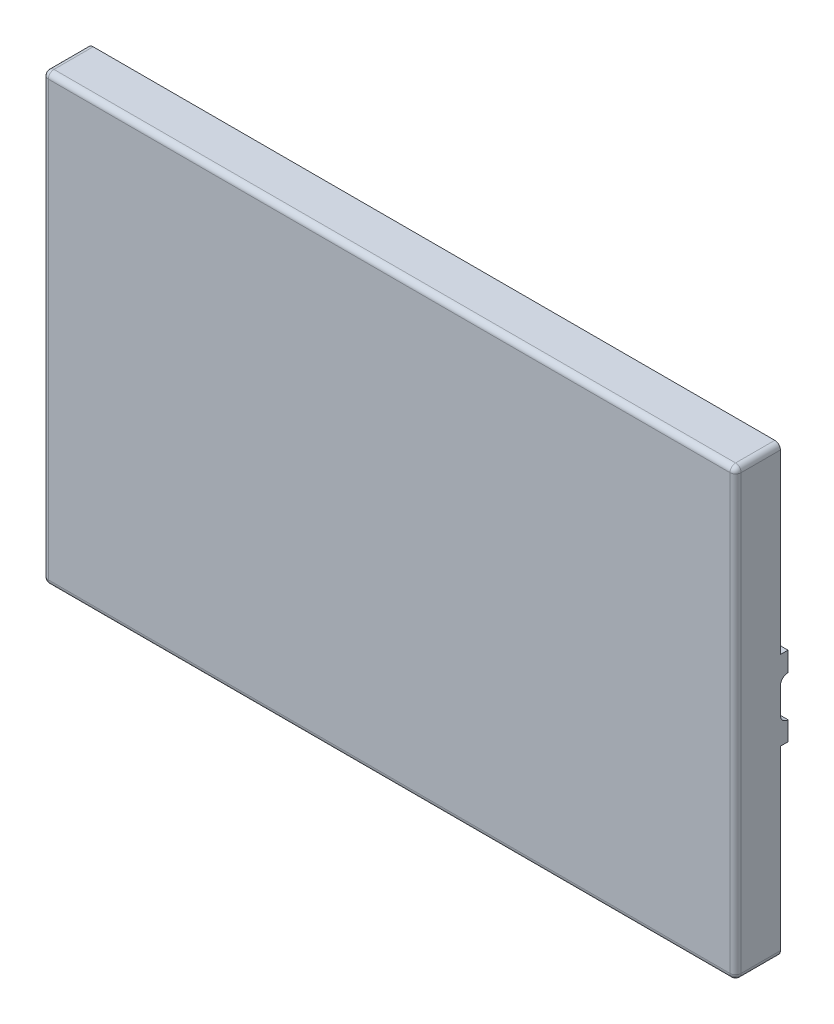
SolidWorks part; units mm, degrees
ref_plane "Front Plane" through (0, 0, 0) normal (0, 0, 1) x (1, 0, 0)
ref_plane "Top Plane" through (0, 0, 0) normal (0, 1, 0) x (1, 0, 0)
ref_plane "Right Plane" through (0, 0, 0) normal (1, 0, 0) x (0, 0, -1)
sketch "Sketch1" plane through (0, 0, 0) normal (0, 0, 1) x (1, 0, 0)
  line L1 (-63.6291, -87.8864) -> (-220.6429, -87.8864)
  line L2 (-63.6291, -87.8864) -> (-63.6291, -188.6926)
  line L3 (-63.6291, -188.6926) -> (-220.6429, -188.6926)
  line L4 (-220.6429, -87.8864) -> (-220.6429, -188.6926)
extrude "Boss-Extrude1" add sketch "Sketch1" along normal blind 10.16
sketch "Sketch2" plane through (0, 0, 0) normal (0, 0, -1) x (-1, 0, 0)
  line L8 (69.9791, -94.2364) -> (69.9791, -182.3426)
  line L9 (69.9791, -182.3426) -> (214.2929, -182.3426)
  line L10 (214.2929, -182.3426) -> (214.2929, -94.2364)
  line L11 (214.2929, -94.2364) -> (69.9791, -94.2364)
  line L12 (69.9791, -94.2364) -> (69.9791, -182.3426)
  line L13 (69.9791, -182.3426) -> (214.2929, -182.3426)
  line L14 (214.2929, -182.3426) -> (214.2929, -94.2364)
  line L15 (214.2929, -94.2364) -> (69.9791, -94.2364)
  dimension "D1" = 6.35
extrude "Cut-Extrude1" cut sketch "Sketch2" against normal blind 3.81
sketch "Sketch3" plane through (0, 0, 3.81) normal (0, 0, -1) x (-1, 0, 0)
  circle A6 centre (109.2991, -111.9901) radius 1.373
  circle A7 centre (156.2491, -111.9901) radius 1.373
  circle A8 centre (156.2491, -136.5001) radius 1.373
  circle A9 centre (109.2991, -136.5001) radius 1.373
  dimension "D1" = 2.746
  dimension "D2" = 2.746
  dimension "D3" = 2.746
  dimension "D4" = 2.746
extrude "Boss-Extrude2" add sketch "Sketch3" along normal blind 13.208
sketch "Sketch4" plane through (0, 0, 3.81) normal (0, 0, -1) x (-1, 0, 0)
  line L0 (106.1041, -98.8201) -> (207.7041, -98.8201) construction
  line L9 (112.4541, -105.1701) -> (191.2741, -105.1701)
  line L10 (112.4541, -105.1701) -> (112.4541, -143.2701)
  line L11 (112.4541, -143.2701) -> (201.3541, -143.2701)
  line L12 (201.3541, -110.2701) -> (201.3541, -143.2701)
  line L18 (106.1041, -149.6201) -> (106.1041, -98.8201) construction
  line L21 (207.7041, -98.8201) -> (207.7041, -149.6201) construction
  line L23 (152.8358, -98.8201) -> (152.8358, -105.1701) construction
  line L25 (207.7041, -122.8794) -> (201.3541, -122.8794) construction
  line L26 (112.4541, -122.0504) -> (106.1041, -122.0504) construction
  line L28 (154.4491, -108.8151) -> (115.6291, -108.8151)
  line L29 (154.4491, -108.8151) -> (154.4491, -139.6751)
  line L30 (154.4491, -139.6751) -> (115.6291, -139.6751)
  line L31 (115.6291, -108.8151) -> (115.6291, -139.6751)
  line L35 (191.2741, -105.1701) -> (191.2741, -110.2701)
  line L36 (191.2741, -110.2701) -> (201.3541, -110.2701)
  line L38 (201.1801, -107.7301) -> (199.1481, -107.7301) construction
  line L39 (193.8141, -107.4761) -> (193.8141, -105.4441) construction
  circle A6 centre (109.2991, -111.9901) radius 1.905
  circle A7 centre (109.2991, -136.5001) radius 1.905
  circle A11 centre (117.2591, -111.5201) radius 0.51 construction
  circle A12 centre (152.8191, -111.5201) radius 0.51 construction
  dimension "D2" = 6.35
  dimension "D3" = 6.35
  dimension "D4" = 6.35
  dimension "D14" = 2.54
  dimension "D6" = 3.81
  dimension "D7" = 3.81
  dimension "D8" = 1.63
  dimension "D9" = 1.63
  dimension "D10" = 3.645
  dimension "D11" = 3.175
  dimension "D12" = 2.54
  dimension "D15" = 3.595
extrude "Boss-Extrude3" add sketch "Sketch4" along normal blind 3.556
sketch "Sketch5" plane through (0, -87.8864, 0) normal (0, 1, 0) x (1, 0, 0)
  line L0 (-63.6291, 0) -> (-220.6429, 0) construction
  line L1 (-211.1977, 23.3785) -> (-70.747, 23.3785)
  line L2 (-211.1977, 23.3785) -> (-211.1977, 2.3813)
  line L3 (-211.1977, 2.3813) -> (-70.747, 2.3812)
  line L4 (-70.747, 23.3785) -> (-70.747, 2.3812)
  dimension "D1" = 2.3813
extrude "Cut-Extrude2" cut sketch "Sketch5" against normal blind 61.722
sketch "Sketch6" plane through (0, 0, 3.81) normal (0, 0, -1) x (-1, 0, 0)
  line L1 (69.9791, -182.3426) -> (73.1541, -182.3426)
  line L2 (69.9791, -182.3426) -> (69.9791, -179.1676)
  line L3 (69.9791, -179.1676) -> (73.1541, -179.1676)
  line L4 (73.1541, -182.3426) -> (73.1541, -179.1676)
  dimension "D1" = 3.175
  dimension "D2" = 3.175
extrude "Boss-Extrude4" add sketch "Sketch6" along normal blind 6.985
sketch "Sketch7" plane through (0, 0, -3.175) normal (0, 0, -1) x (-1, 0, 0)
  line L1 (73.1541, -179.1676) -> (71.5666, -179.1676)
  line L2 (73.1541, -179.1676) -> (73.1541, -180.7551)
  line L3 (73.1541, -180.7551) -> (71.5666, -180.7551)
  line L4 (71.5666, -179.1676) -> (71.5666, -180.7551)
  dimension "D1" = 1.5875
  dimension "D2" = 1.5875
extrude "Cut-Extrude3" cut sketch "Sketch7" against normal blind 6.985
ref_plane "Plane1" through (0, -138.2895, 0) normal (0, -1, 0) x (-1, 0, 0)
mirror "Mirror1" about plane through (0, -138.2895, 0) normal (0, -1, 0) of "Cut-Extrude3", "Boss-Extrude4"
ref_plane "Plane2" through (-142.136, 0, 0) normal (1, 0, 0) x (0, 0, -1)
mirror "Mirror2" about plane through (-142.136, 0, 0) normal (1, 0, 0) of "Mirror1", "Cut-Extrude3", "Boss-Extrude4"
sketch "Sketch8" plane through (0, 0, -3.175) normal (0, 0, -1) x (-1, 0, 0)
  line L0 (69.9791, -179.1676) -> (70.1775, -179.1676)
  line L1 (71.5666, -179.1676) -> (69.9791, -179.1676) construction
  line L2 (70.1775, -179.1676) -> (70.1775, -182.1442)
  line L3 (70.1775, -182.1442) -> (73.1541, -182.1442)
  line L4 (73.1541, -182.3426) -> (73.1541, -180.7551) construction
  line L5 (73.1541, -182.1442) -> (73.1541, -182.3426)
  line L6 (73.1541, -182.3426) -> (69.9791, -182.3426)
  line L7 (69.9791, -182.3426) -> (69.9791, -179.1676)
  dimension "D1" = 0.1984
  dimension "D2" = 0.1984
extrude "Cut-Extrude4" cut sketch "Sketch8" against normal up to surface (3.175 mm away) up to face at (-142.136, -138.2895, 0)
mirror "Mirror3" about plane through (-142.136, 0, 0) normal (1, 0, 0) of "Cut-Extrude4" second plane through (0, -138.2895, 0) second plane normal (0, -1, 0)
fillet "Fillet1" radius 1.27 8 edges at (-63.6291, -188.6926, 5.08) (-142.136, -188.6926, 10.16) (-220.6429, -188.6926, 5.08) (-220.6429, -138.2895, 10.16) (-220.6429, -87.8864, 5.08) (-142.136, -87.8864, 10.16) (-63.6291, -138.2895, 10.16) (-63.6291, -87.8864, 5.08)
sketch "Sketch9" plane through (0, 0, 3.81) normal (0, 0, -1) x (-1, 0, 0)
  line L0 (204.371, -174.0082) -> (180.5585, -174.0082)
  line L1 (204.371, -174.0082) -> (204.371, -158.1332)
  line L2 (204.371, -158.1332) -> (180.5585, -158.1332)
  line L3 (180.5585, -174.0082) -> (180.5585, -158.1332)
  line L4 (214.2929, -179.1676) -> (214.2929, -97.4114) construction
  line L5 (73.1541, -182.3426) -> (211.1179, -182.3426) construction
  dimension "D1" = 15.875
  dimension "D2" = 9.9219
  dimension "D3" = 8.3344
extrude "Boss-Extrude5" add sketch "Sketch9" along normal blind 11.4935
sketch "Sketch10" plane through (-63.6291, 0, 0) normal (1, 0, 0) x (0, 0, -1)
  line L0 (0, -187.4226) -> (0, -89.1564) construction
  line L1 (-0.7937, -129.1614) -> (8.4675, -129.1614)
  line L2 (-0.7937, -129.1614) -> (-0.7937, -147.4176)
  line L3 (-0.7937, -147.4176) -> (8.4675, -147.4176)
  line L4 (8.4675, -129.1614) -> (8.4675, -147.4176)
  line L5 (0, -89.1564) -> (-8.89, -89.1564) construction
  line L6 (-0.7937, -129.1614) -> (-0.7937, -89.1564) construction
  line L7 (-0.7937, -147.4176) -> (-0.7937, -187.4226) construction
  line L8 (-8.89, -187.4226) -> (0, -187.4226) construction
  dimension "D1" = 18.2562
  dimension "D2" = 0.7937
extrude "Cut-Extrude5" cut sketch "Sketch10" against normal blind 13.97 from offset 1.5875 offset against normal yes
sketch "Sketch12" plane through (0, 0, 3.81) normal (0, 0, -1) x (-1, 0, 0)
  line L1 (69.9791, -129.1614) -> (87.7591, -129.1614)
  line L2 (69.9791, -129.1614) -> (69.9791, -147.4176)
  line L3 (69.9791, -147.4176) -> (87.7591, -147.4176)
  line L4 (87.7591, -129.1614) -> (87.7591, -147.4176)
  dimension "D1" = 17.78
extrude "Boss-Extrude6" add sketch "Sketch12" along normal up to surface (3.0162 mm away) up to face at (-67.5979, -138.2895, 0.7937)
sketch "Sketch13" plane through (0, 0, 3.81) normal (0, 0, -1) x (-1, 0, 0)
  line L1 (91.6754, -134.2414) -> (94.8504, -134.2414)
  line L2 (91.6754, -134.2414) -> (91.6754, -142.3376)
  line L3 (91.6754, -142.3376) -> (94.8504, -142.3376)
  line L4 (94.8504, -134.2414) -> (94.8504, -142.3376)
  line L5 (87.7591, -129.1614) -> (101.5052, -129.1614) construction
  line L6 (87.7591, -147.4176) -> (99.914, -147.4176) construction
  line L7 (93.2629, -142.3376) -> (93.2629, -147.4176) construction
  line L8 (93.2629, -129.1614) -> (93.2629, -134.2414) construction
  line L9 (87.7591, -129.1614) -> (87.7591, -147.4176) construction
  dimension "D1" = 3.9162
  dimension "D2" = 3.175
  dimension "D3" = 5.08
extrude "Boss-Extrude7" add sketch "Sketch13" along normal blind 5.08
sketch "Sketch14" plane through (-63.6291, 0, 0) normal (1, 0, 0) x (0, 0, -1)
  line L6 (0, -129.2884) -> (0, -135.4466)
  line L7 (0, -187.4226) -> (0, -89.1564) construction
  line L10 (0, -147.2906) -> (1.7169, -147.2906)
  line L11 (1.7169, -147.2906) -> (1.7169, -142.9435)
  line L12 (0, -141.2266) -> (0, -147.2906)
  line L13 (1.7169, -133.7297) -> (1.7169, -129.2884)
  line L14 (1.7169, -129.2884) -> (0, -129.2884)
  line L15 (3.4337, -135.4466) -> (1.2516, -135.4466) construction
  line L17 (3.4337, -141.2266) -> (2.7224, -141.2266) construction
  arc A1 (1.7169, -142.9435) -> (0, -141.2266) centre (1.7169, -141.2266) cw
  arc A2 (1.7169, -133.7297) -> (0, -135.4466) centre (1.7169, -135.4466) ccw
  dimension "D1" = 6.1583
  dimension "D2" = 6.064
extrude "Boss-Extrude9" add sketch "Sketch14" against normal up to surface (1.5875 mm away) up to face at (-65.2166, -138.2895, 0.3969)
sketch "Sketch17" plane through (0, 0, 3.81) normal (0, 0, -1) x (-1, 0, 0)
  line L0 (155.5098, -182.3426) -> (155.5098, -174.0082) construction
  line L1 (155.1585, -170.1982) -> (155.1585, -152.7834) construction
  line L2 (180.5585, -158.1332) -> (180.5585, -174.0082) construction
  line L3 (142.4585, -174.0082) -> (167.8585, -174.0082)
  line L4 (142.4585, -174.0082) -> (142.4585, -170.1982)
  line L5 (142.4585, -170.1982) -> (167.8585, -170.1982)
  line L6 (167.8585, -174.0082) -> (167.8585, -170.1982)
  line L7 (142.4585, -152.7834) -> (167.8585, -152.7834)
  line L8 (142.4585, -152.7834) -> (142.4585, -148.9734)
  line L9 (142.4585, -148.9734) -> (167.8585, -148.9734)
  line L10 (167.8585, -152.7834) -> (167.8585, -148.9734)
  line L11 (73.1541, -182.3426) -> (211.1179, -182.3426) construction
  line L12 (73.1541, -182.3426) -> (211.1179, -182.3426) construction
  line L13 (136.545, -161.4908) -> (173.7719, -161.4908) construction
  line L14 (173.7719, -158.3158) -> (177.5819, -158.3158)
  line L15 (173.7719, -158.3158) -> (173.7719, -164.6658)
  line L16 (173.7719, -164.6658) -> (177.5819, -164.6658)
  line L17 (177.5819, -158.3158) -> (177.5819, -164.6658)
  line L18 (132.735, -158.3158) -> (136.545, -158.3158)
  line L19 (132.735, -158.3158) -> (132.735, -164.6658)
  line L20 (132.735, -164.6658) -> (136.545, -164.6658)
  line L21 (136.545, -158.3158) -> (136.545, -164.6658)
  line L23 (142.4585, -152.7834) -> (142.4585, -170.1982) construction
  line L24 (167.8585, -152.7834) -> (167.8585, -170.1982) construction
  line L25 (136.545, -159.4524) -> (142.4585, -159.4524) construction
  line L26 (167.8585, -160.6282) -> (173.7719, -160.6282) construction
  point P34 (136.545, -161.4908)
  point P35 (155.1585, -161.4908)
  point P36 (155.1585, -161.4908)
  dimension "D1" = 12.7
  dimension "D2" = 8.3344
  dimension "D3" = 3.81
  dimension "D4" = 3.81
  dimension "D5" = 17.4149
  dimension "D6" = 25.4
  dimension "D7" = 37.2269
  dimension "D8" = 3.81
  dimension "D9" = 6.35
extrude "Boss-Extrude10" add sketch "Sketch17" along normal blind 5.3658
sketch "Sketch18" plane through (0, 0, 3.81) normal (0, 0, -1) x (-1, 0, 0)
  line L0 (136.545, -152.7834) -> (155.595, -152.7834)
  line L1 (136.545, -152.7834) -> (136.545, -170.1982)
  line L2 (136.545, -170.1982) -> (155.595, -170.1982)
  line L3 (155.595, -152.7834) -> (155.595, -170.1982)
  line L4 (167.8585, -170.1982) -> (142.4585, -170.1982) construction
  line L6 (136.545, -164.6658) -> (136.545, -158.3158) construction
  line L7 (142.4585, -152.7834) -> (167.8585, -152.7834) construction
  line L8 (167.4219, -152.7834) -> (173.7719, -152.7834)
  line L9 (167.4219, -152.7834) -> (167.4219, -170.1982)
  line L10 (167.4219, -170.1982) -> (173.7719, -170.1982)
  line L11 (173.7719, -152.7834) -> (173.7719, -170.1982)
  line L12 (173.7719, -158.3158) -> (173.7719, -164.6658) construction
  dimension "D1" = 19.05
  dimension "D2" = 6.35
extrude "Boss-Extrude11" add sketch "Sketch18" along normal up to surface (3.556 mm away) up to face at (-157.6221, -111.9901, 0.254)
sketch "Sketch19" plane through (0, -188.6926, 0) normal (0, -1, 0) x (1, 0, 0)
  line L0 (-219.3729, 0) -> (-64.8991, 0) construction
  line L1 (-151.038, -4.3498) -> (-164.8493, -4.3498)
  line L2 (-151.038, -4.3498) -> (-151.038, 0)
  line L3 (-151.038, 0) -> (-164.8493, 0)
  line L4 (-164.8493, -4.3498) -> (-164.8493, 0)
  line L5 (-164.8493, -2.1749) -> (-170.7706, -2.1749) construction
  line L6 (-170.7706, 0) -> (-170.7706, -10.4775) construction
  line L7 (-151.038, -2.1749) -> (-145.1166, -2.1749) construction
  line L8 (-145.1166, -10.4775) -> (-145.1166, 0) construction
  dimension "D1" = 4.3498
  dimension "D2" = 13.8113
  dimension "D3" = 5.9214
extrude "Boss-Extrude12" add sketch "Sketch19" against normal up to surface (6.35 mm away) up to face at (-142.136, -182.3426, 1.905)
sketch "Sketch21" plane through (0, 0, 0) normal (0, 0, -1) x (-1, 0, 0)
  line L0 (73.1541, -182.3426) -> (151.038, -182.3426) construction
  line L1 (151.038, -188.6926) -> (145.2436, -188.6926)
  line L2 (151.038, -188.6926) -> (151.038, -182.3426)
  line L3 (151.038, -182.3426) -> (145.2436, -182.3426)
  line L4 (145.2436, -188.6926) -> (145.2436, -182.3426)
  line L5 (164.8493, -182.3426) -> (211.1179, -182.3426) construction
  line L6 (164.8493, -188.6926) -> (170.6436, -188.6926)
  line L7 (164.8493, -188.6926) -> (164.8493, -182.3426)
  line L8 (164.8493, -182.3426) -> (170.6436, -182.3426)
  line L9 (170.6436, -188.6926) -> (170.6436, -182.3426)
  dimension "D1" = 5.7944
  dimension "D2" = 5.7944
  dimension "D3" = 25.4
extrude "Boss-Extrude13" add sketch "Sketch21" along normal up to surface (10.4775 mm away)
sketch "Sketch22" plane through (0, 0, -10.4775) normal (0, 0, -1) x (-1, 0, 0)
  line L0 (157.9436, -185.1207) -> (157.9436, -182.3426) construction
  line L1 (148.0218, -185.1207) -> (167.8655, -185.1207)
  line L2 (148.0218, -185.1207) -> (148.0218, -185.9145)
  line L3 (148.0218, -185.9145) -> (167.8655, -185.9145)
  line L4 (167.8655, -185.1207) -> (167.8655, -185.9145)
  line L5 (151.038, -182.3426) -> (164.8493, -182.3426) construction
  line L6 (157.9436, -185.9145) -> (157.9436, -188.6926) construction
  line L7 (164.8493, -188.6926) -> (151.038, -188.6926) construction
  line L8 (148.0218, -185.5176) -> (145.2436, -185.5176) construction
  line L9 (145.2436, -182.3426) -> (145.2436, -188.6926) construction
  line L10 (167.8655, -185.5176) -> (170.6436, -185.5176) construction
  line L11 (170.6436, -188.6926) -> (170.6436, -182.3426) construction
  line L12 (73.1541, -182.3426) -> (211.1179, -182.3426) construction
  dimension "D1" = 19.8438
  dimension "D2" = 0.7937
extrude "Cut-Extrude6" cut sketch "Sketch22" against normal up to surface (6.1277 mm away) up to face at (-157.9436, -185.5176, -4.3497)
sketch "Sketch23" plane through (0, 0, -1.5558) normal (0, 0, -1) x (-1, 0, 0)
  line L0 (136.545, -158.3158) -> (132.735, -158.3158) construction
  line L1 (134.64, -158.3158) -> (132.735, -158.3158)
  line L2 (134.64, -158.3158) -> (134.64, -164.6658)
  line L3 (134.64, -164.6658) -> (132.735, -164.6658)
  line L4 (132.735, -158.3158) -> (132.735, -164.6658)
  line L5 (142.4585, -170.1982) -> (142.4585, -174.0082) construction
  line L6 (142.4585, -172.1032) -> (167.8585, -172.1032)
  line L7 (142.4585, -172.1032) -> (142.4585, -174.0082)
  line L8 (142.4585, -174.0082) -> (167.8585, -174.0082)
  line L9 (167.8585, -172.1032) -> (167.8585, -174.0082)
  line L10 (177.5819, -158.3158) -> (173.7719, -158.3158) construction
  line L11 (175.6769, -158.3158) -> (177.5819, -158.3158)
  line L12 (175.6769, -158.3158) -> (175.6769, -164.6658)
  line L13 (175.6769, -164.6658) -> (177.5819, -164.6658)
  line L14 (177.5819, -158.3158) -> (177.5819, -164.6658)
  line L15 (167.8585, -152.7834) -> (167.8585, -148.9734) construction
  line L16 (142.4585, -148.9734) -> (167.8585, -148.9734)
  line L17 (142.4585, -148.9734) -> (142.4585, -150.8784)
  line L18 (142.4585, -150.8784) -> (167.8585, -150.8784)
  line L19 (167.8585, -148.9734) -> (167.8585, -150.8784)
extrude "Cut-Extrude7" cut sketch "Sketch23" against normal up to surface (5.3658 mm away) up to face at (-135.0391, -124.2451, 3.81)
